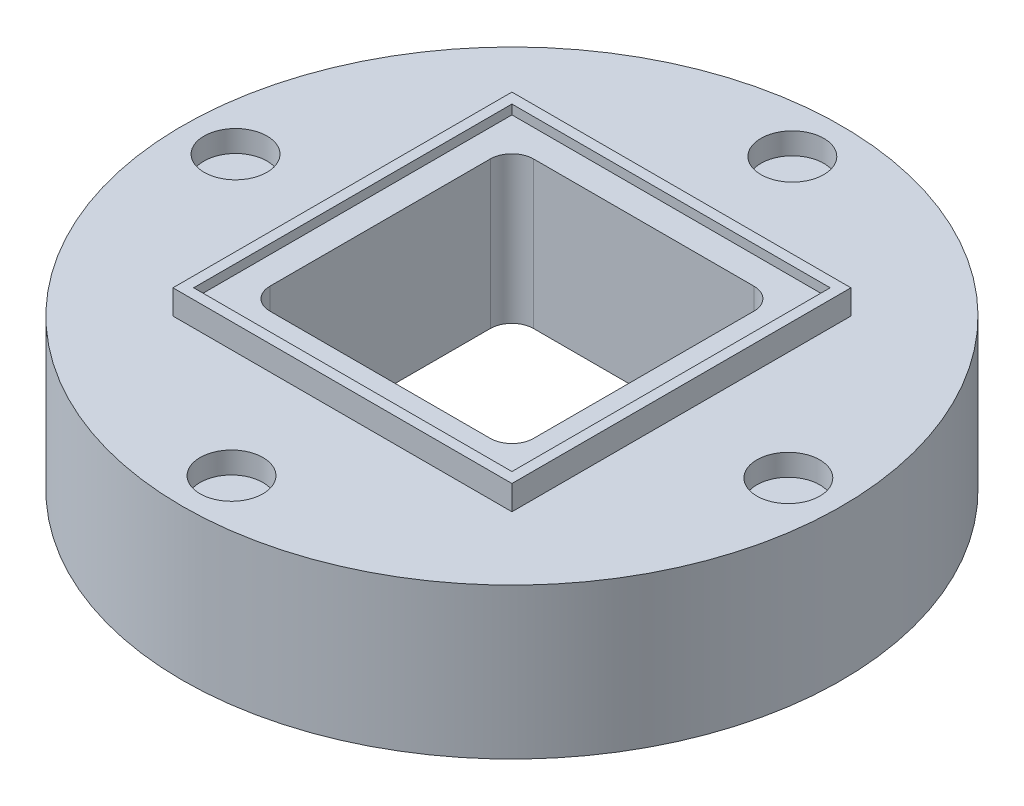
SolidWorks part; units mm, degrees
material "ABS"
ref_plane "Front Plane" through (0, 0, 0) normal (0, 0, 1) x (1, 0, 0)
ref_plane "Top Plane" through (0, 0, 0) normal (0, 1, 0) x (1, 0, 0)
ref_plane "Right Plane" through (0, 0, 0) normal (1, 0, 0) x (0, 0, -1)
sketch "Sketch1" plane through (0, 0, 0) normal (0, 1, 0) x (1, 0, 0)
  circle A0 centre (0, 0) radius 17.5
  dimension "D1" = 35
extrude "Boss-Extrude1" add sketch "Sketch1" along normal blind 8
sketch "Sketch5" plane through (0, 0, 0) normal (0, -1, 0) x (1, 0, 0)
  circle A2 centre (0, 0) radius 16.5
  circle A3 centre (0, 0) radius 16.5
  dimension "D1" = 1
extrude "Cut-Extrude2" cut sketch "Sketch5" against normal blind 1
sketch "Sketch11" plane through (0, 8, 0) normal (0, 1, 0) x (1, 0, 0)
  line L0 (0, 17.5) -> (0, 16.45) construction
  circle A0 centre (0, 0) radius 17.5 construction
  circle A1 centre (0.1067, 14.7834) radius 1.67
  dimension "D2" = 3.34
  dimension "D1" = 1.05
extrude "Cut-Extrude5" cut sketch "Sketch11" against normal blind 1.15
pattern_circular "CirPattern1" count 4 over 360 about axis through (0, 0, 0) along (0, 1, 0) of "Cut-Extrude5"
sketch "Sketch13" plane through (0, 8, 0) normal (0, 1, 0) x (1, 0, 0)
  line L1 (9, -9) -> (-9, -9)
  line L2 (9, -9) -> (9, 9)
  line L3 (9, 9) -> (-9, 9)
  line L4 (-9, -9) -> (-9, 9)
  line L5 (9, -9) -> (-9, 9) construction
  line L6 (9, 9) -> (-9, -9) construction
  line L7 (8.45, -8.45) -> (-8.45, -8.45)
  line L8 (8.45, -8.45) -> (8.45, 8.45)
  line L9 (8.45, 8.45) -> (-8.45, 8.45)
  line L10 (-8.45, -8.45) -> (-8.45, 8.45)
  line L11 (8.45, -8.45) -> (-8.45, 8.45) construction
  line L12 (8.45, 8.45) -> (-8.45, -8.45) construction
  point P0 (0, 0)
  point P7 (0, 0)
  point P28 (0, 0)
  dimension "D1" = 18
  dimension "D3" = 16.9
extrude "Boss-Extrude3" add sketch "Sketch13" along normal blind 1.3 contours L4 L1 L2 L3 L7 L10 L9 L8
sketch "Sketch12" plane through (0, 8, 0) normal (0, 1, 0) x (1, 0, 0)
  line L0 (9, -9) -> (9, 9) construction
  line L1 (-9, 9) -> (9, 9)
  line L2 (-9, 9) -> (-9, -9)
  line L3 (-9, -9) -> (9, -9)
  line L4 (9, 9) -> (9, -9)
  line L5 (-9, 9) -> (9, -9) construction
  line L6 (-9, -9) -> (9, 9) construction
  point P0 (0, 0)
  point P1 (0, 0)
extrude "Boss-Extrude2" add sketch "Sketch12" along normal blind 0.8
sketch "Sketch14" plane through (0, 8.8, 0) normal (0, 1, 0) x (1, 0, 0)
  line L0 (5.85, 7) -> (5.85, 5.85) construction
  line L1 (-7, -7) -> (7, -7)
  line L2 (-7, -7) -> (-7, 7)
  line L3 (-7, 7) -> (7, 7)
  line L4 (7, -7) -> (7, 7)
  line L5 (-7, -7) -> (7, 7) construction
  line L6 (-7, 7) -> (7, -7) construction
  line L7 (5.85, 5.85) -> (7, 5.85) construction
  arc A0 (5.85, 7) -> (7, 5.85) centre (5.85, 5.85) cw
  arc A1 (7, -5.85) -> (5.85, -7) centre (5.85, -5.85) cw
  arc A2 (-5.85, -7) -> (-7, -5.85) centre (-5.85, -5.85) cw
  arc A3 (-7, 5.85) -> (-5.85, 7) centre (-5.85, 5.85) cw
  point P0 (0, 0)
  point P22 (0, 0)
  dimension "D1" = 14
  dimension "D2" = 14
  dimension "D3" = 1.15
  dimension "D4" = 4
extrude "Cut-Extrude6" cut sketch "Sketch14" against normal through all contours A3 L2 A2 L1 A1 L4 A0 L3
